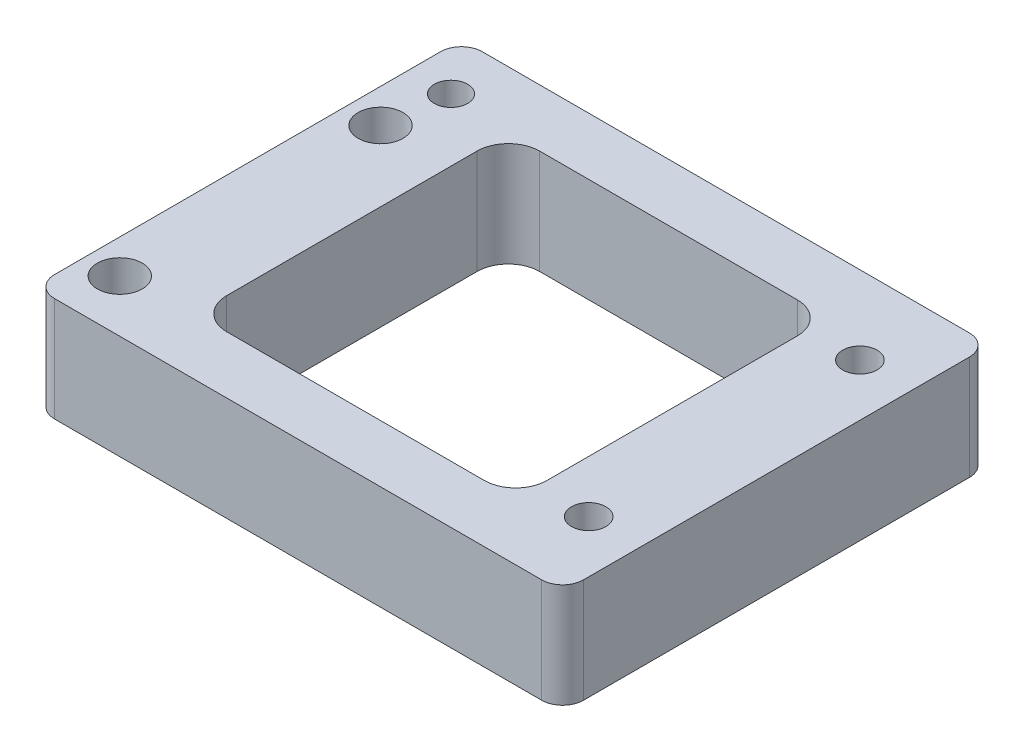
SolidWorks part; units mm, degrees
material "5052-H34"
ref_plane "正面" through (0, 0, 0) normal (0, 0, 1) x (1, 0, 0)
ref_plane "平面" through (0, 0, 0) normal (0, 1, 0) x (1, 0, 0)
ref_plane "右側面" through (0, 0, 0) normal (1, 0, 0) x (0, 0, -1)
sketch "ｽｹｯﾁ2" plane through (0, 0, 0) normal (0, 1, 0) x (1, 0, 0)
  line L1 (0, 0) -> (50.7, 0)
  line L2 (0, 0) -> (0, 41)
  line L3 (0, 41) -> (50.7, 41)
  line L10 (50.7, 0) -> (50.7, 41)
  line L13 (50.7, 20.5) -> (0, 20.5) construction
  line L15 (4, 41) -> (4, 0) construction
  line L16 (10, 5.5) -> (40.7, 5.5)
  line L17 (10, 5.5) -> (10, 35.5)
  line L18 (10, 35.5) -> (40.7, 35.5)
  line L19 (40.7, 5.5) -> (40.7, 35.5)
  line L20 (10, 5.5) -> (40.7, 35.5) construction
  line L21 (10, 35.5) -> (40.7, 5.5) construction
  circle A3 centre (4, 36) radius 1.6
  circle A4 centre (3.25, 30) radius 2.15
  circle A5 centre (3.25, 5) radius 2.15
  circle A8 centre (45.7, 33.5) radius 1.65
  circle A9 centre (45.7, 7.5) radius 1.65
  point P11 (25.35, 20.5)
  dimension "D9" = 5
  dimension "D10" = 30
  dimension "D12" = 5
  dimension "D14" = 4.3
  dimension "D15" = 3.25
  dimension "D16" = 25
  dimension "D4" = 3.2
  dimension "D5" = 5
  dimension "D6" = 3.3
  dimension "D7" = 5
  dimension "D8" = 7.5
  dimension "D2" = 41
  dimension "D3" = 50.7
  dimension "D11" = 4
extrude "ﾎﾞｽ - 押し出し1" add sketch "ｽｹｯﾁ2" along normal blind 10
fillet "ﾌｨﾚｯﾄ1" radius 2 4 edges at (0, 5, -41) (0, 5, 0) (50.7, 5, -41) (50.7, 5, 0)
fillet "ﾌｨﾚｯﾄ2" radius 3 4 edges at (10, 5, -5.5) (40.7, 5, -5.5) (40.7, 5, -35.5) (10, 5, -35.5)
